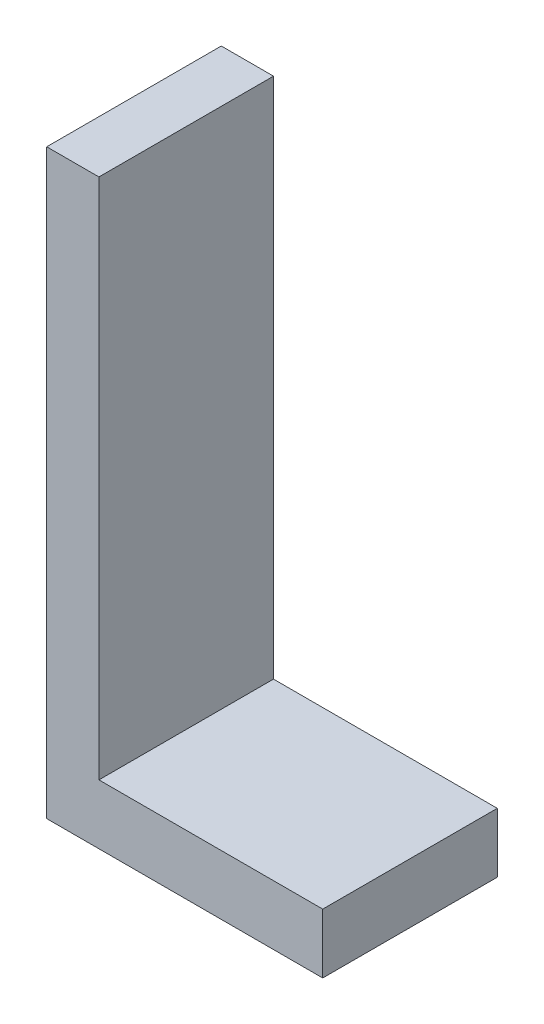
SolidWorks part; units mm, degrees
ref_plane "Plan de face" through (0, 0, 0) normal (0, 0, 1) x (1, 0, 0)
ref_plane "Plan de dessus" through (0, 0, 0) normal (0, 1, 0) x (1, 0, 0)
ref_plane "Plan de droite" through (0, 0, 0) normal (1, 0, 0) x (0, 0, -1)
sketch "Esquisse1" plane through (0, 0, 0) normal (0, 0, 1) x (1, 0, 0)
  text T0 "L" font "Century Gothic" height 5
extrude "Boss.-Extru.1" add sketch "Esquisse1" along normal blind 1.5
